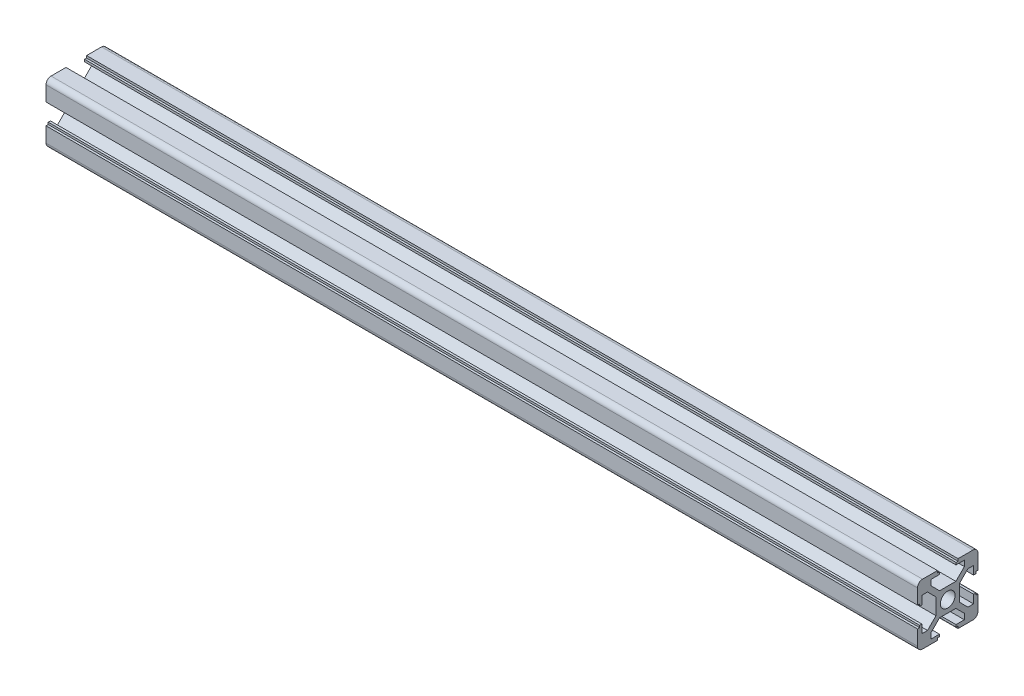
SolidWorks part; units mm, degrees
material "6061-T6 (SS)"
ref_plane "Front Plane" through (0, 0, 0) normal (0, 0, 1) x (1, 0, 0)
ref_plane "Top Plane" through (0, 0, 0) normal (0, 1, 0) x (1, 0, 0)
ref_plane "Right Plane" through (0, 0, 0) normal (1, 0, 0) x (0, 0, -1)
sketch3d "3DSketch1"
  line L0 (-215.9, 0, 0) -> (215.9, 0, 0)
  point P4 (0, 0, 0)
  dimension "D1" = 431.8
other "Boschrexroth BOSCH_30X30_V2(1)"
ref_plane "Plane1" through (-215.9, 0, 0) normal (1, 0, 0) x (0, 0, -1)
sketch "Sketch1" plane through (-215.9, 0, 0) normal (1, 0, 0) x (0, 0, -1)
  line L0 (0, 0) -> (0, 15) construction
  line L1 (0, 5.8) -> (-4.03, 5.8)
  line L2 (-15, 0) -> (0, 0) construction
  line L3 (-4.03, 5.8) -> (-8.25, 10.02)
  line L4 (-8.25, 10.02) -> (-8.25, 12.8)
  line L5 (-8.25, 12.8) -> (-4.1, 12.8)
  line L6 (-4.1, 12.8) -> (-4.1, 13.9)
  line L7 (-4.1, 13.9) -> (-5.1, 13.9)
  line L8 (-5.1, 13.9) -> (-5.1, 15)
  line L9 (-5.1, 15) -> (-12.5, 15)
  line L10 (-15, 12.5) -> (-15, 5.1)
  line L11 (-15, 5.1) -> (-13.9, 5.1)
  line L12 (-13.9, 5.1) -> (-13.9, 4.1)
  line L13 (-13.9, 4.1) -> (-12.8, 4.1)
  line L14 (-12.8, 4.1) -> (-12.8, 8.25)
  line L15 (-12.8, 8.25) -> (-10.02, 8.25)
  line L16 (-10.02, 8.25) -> (-5.8, 4.03)
  line L17 (-5.8, 4.03) -> (-5.8, 0)
  line L18 (4.1, 13.9) -> (5.1, 13.9)
  line L19 (5.1, 13.9) -> (5.1, 15)
  line L20 (10.02, 8.25) -> (5.8, 4.03)
  line L21 (12.8, 8.25) -> (10.02, 8.25)
  line L22 (12.8, 4.1) -> (12.8, 8.25)
  line L23 (13.9, 4.1) -> (12.8, 4.1)
  line L24 (13.9, 5.1) -> (13.9, 4.1)
  line L25 (15, 5.1) -> (13.9, 5.1)
  line L26 (15, 12.5) -> (15, 5.1)
  line L27 (5.1, 15) -> (12.5, 15)
  line L28 (8.25, 12.8) -> (4.1, 12.8)
  line L29 (8.25, 10.02) -> (8.25, 12.8)
  line L30 (4.03, 5.8) -> (8.25, 10.02)
  line L31 (4.1, 13.9) -> (4.1, 12.8)
  line L32 (4.03, 5.8) -> (0, 5.8)
  line L33 (5.8, 4.03) -> (5.8, 0)
  line L34 (4.1, -13.9) -> (4.1, -12.8)
  line L35 (4.1, -13.9) -> (5.1, -13.9)
  line L36 (5.1, -13.9) -> (5.1, -15)
  line L37 (4.03, -5.8) -> (8.25, -10.02)
  line L38 (8.25, -10.02) -> (8.25, -12.8)
  line L39 (8.25, -12.8) -> (4.1, -12.8)
  line L40 (5.1, -15) -> (12.5, -15)
  line L41 (15, -12.5) -> (15, -5.1)
  line L42 (15, -5.1) -> (13.9, -5.1)
  line L43 (13.9, -5.1) -> (13.9, -4.1)
  line L44 (13.9, -4.1) -> (12.8, -4.1)
  line L45 (12.8, -4.1) -> (12.8, -8.25)
  line L46 (12.8, -8.25) -> (10.02, -8.25)
  line L47 (10.02, -8.25) -> (5.8, -4.03)
  line L48 (5.8, 0) -> (5.8, -4.03)
  line L49 (-13.9, -4.1) -> (-12.8, -4.1)
  line L50 (-13.9, -5.1) -> (-13.9, -4.1)
  line L51 (-15, -5.1) -> (-13.9, -5.1)
  line L52 (-10.02, -8.25) -> (-5.8, -4.03)
  line L53 (-12.8, -8.25) -> (-10.02, -8.25)
  line L54 (-12.8, -4.1) -> (-12.8, -8.25)
  line L55 (-15, -12.5) -> (-15, -5.1)
  line L56 (-5.1, -15) -> (-12.5, -15)
  line L57 (-5.1, -13.9) -> (-5.1, -15)
  line L58 (-4.1, -13.9) -> (-5.1, -13.9)
  line L59 (-4.1, -12.8) -> (-4.1, -13.9)
  line L60 (-8.25, -12.8) -> (-4.1, -12.8)
  line L61 (-8.25, -10.02) -> (-8.25, -12.8)
  line L62 (-4.03, -5.8) -> (-8.25, -10.02)
  line L63 (-5.8, 0) -> (-5.8, -4.03)
  line L64 (-4.03, -5.8) -> (4.03, -5.8)
  line L65 (0, 0) -> (15, 0) construction
  line L66 (0, 0) -> (0, -15) construction
  arc A0 (-12.5, 15) -> (-15, 12.5) centre (-12.5, 12.5) ccw
  arc A1 (-15, -12.5) -> (-12.5, -15) centre (-12.5, -12.5) ccw
  arc A2 (12.5, -15) -> (15, -12.5) centre (12.5, -12.5) ccw
  arc A3 (15, 12.5) -> (12.5, 15) centre (12.5, 12.5) ccw
  circle A4 centre (0, 0) radius 3.65
  point P69 (-15, 15)
  point P72 (-15, -15)
  point P75 (15, -15)
  point P78 (15, 15)
  point P79 (-15, 15)
  point P81 (15, 15)
  point P83 (15, -15)
  point P84 (-15, -15)
  point P86 (0, 0)
  dimension "D15" = 2.5
  dimension "D16" = 7.3
  dimension "D1" = 15
  dimension "D2" = 2.2
  dimension "D3" = 1.1
  dimension "D4" = 1
  dimension "D5" = 8.25
  dimension "D6" = 5.1
  dimension "D7" = 7
  dimension "D8" = 2.78
  dimension "D9" = 15
  dimension "D10" = 15
  dimension "D11" = 4.03
  dimension "D12" = 4.03
  dimension "D13" = 2.5032
  dimension "D14" = 9.2
